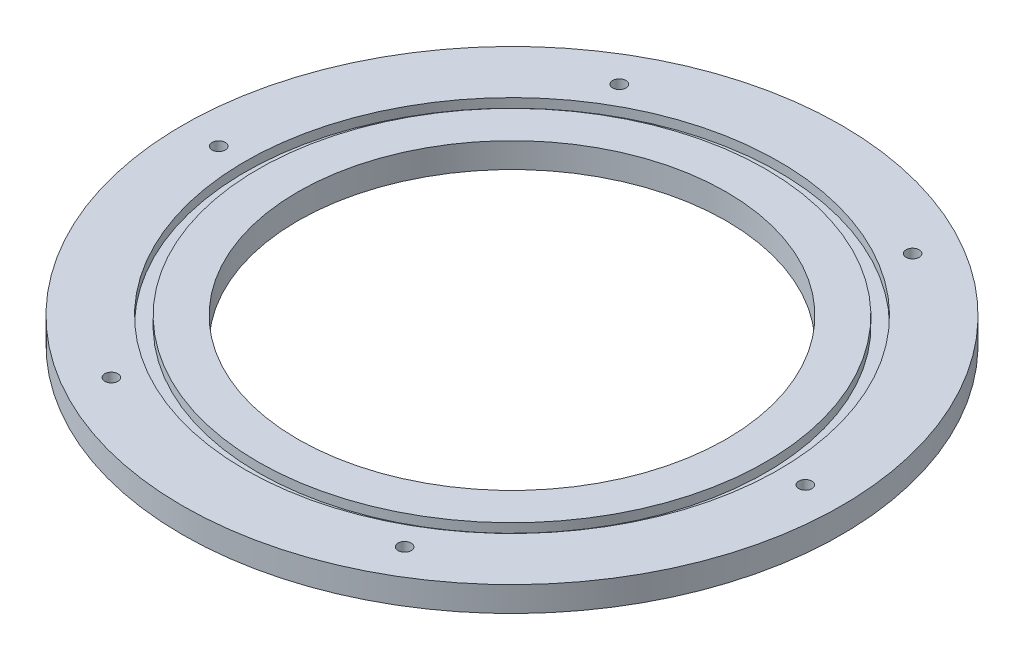
SolidWorks part; units mm, degrees
material "Pine"
ref_plane "Front Plane" through (0, 0, 0) normal (0, 0, 1) x (1, 0, 0)
ref_plane "Top Plane" through (0, 0, 0) normal (0, 1, 0) x (1, 0, 0)
ref_plane "Right Plane" through (0, 0, 0) normal (1, 0, 0) x (0, 0, -1)
sketch "Sketch1" plane through (0, 0, 0) normal (0, 1, 0) x (1, 0, 0)
  circle A0 centre (0, 0) radius 250
  circle A2 centre (0, 0) radius 162.5
  dimension "D1" = 500
  dimension "D2" = 325
extrude "Boss-Extrude1" add sketch "Sketch1" along normal mid plane 19
sketch "Sketch2" plane through (0, 9.5, 0) normal (0, 1, 0) x (1, 0, 0)
  circle A0 centre (0, 0) radius 202.5
  circle A1 centre (0, 0) radius 192.5
  dimension "D1" = 405
  dimension "D2" = 10
extrude "Cut-Extrude1" cut sketch "Sketch2" against normal blind 7
sketch "Sketch3" plane through (0, 9.5, 0) normal (0, 1, 0) x (1, 0, 0)
  line L0 (-1000, 0) -> (49000, 0) construction
  line L1 (0, -1000) -> (0, 49000) construction
  line L2 (-500, -866.0254) -> (24500, 42435.2448) construction
  line L3 (-500, 866.0254) -> (24500, -42435.2448) construction
  circle A0 centre (111.25, 192.6907) radius 5
  circle A1 centre (222.5, 0) radius 5
  circle A2 centre (-111.25, 192.6907) radius 5
  circle A3 centre (-222.5, 0) radius 5
  circle A4 centre (111.25, -192.6907) radius 5
  circle A5 centre (-111.25, -192.6907) radius 5
  dimension "D1" = 10
  dimension "D2" = 10
  dimension "D3" = 222.5
  dimension "D4" = 222.5
extrude "Cut-Extrude2" cut sketch "Sketch3" against normal through all
